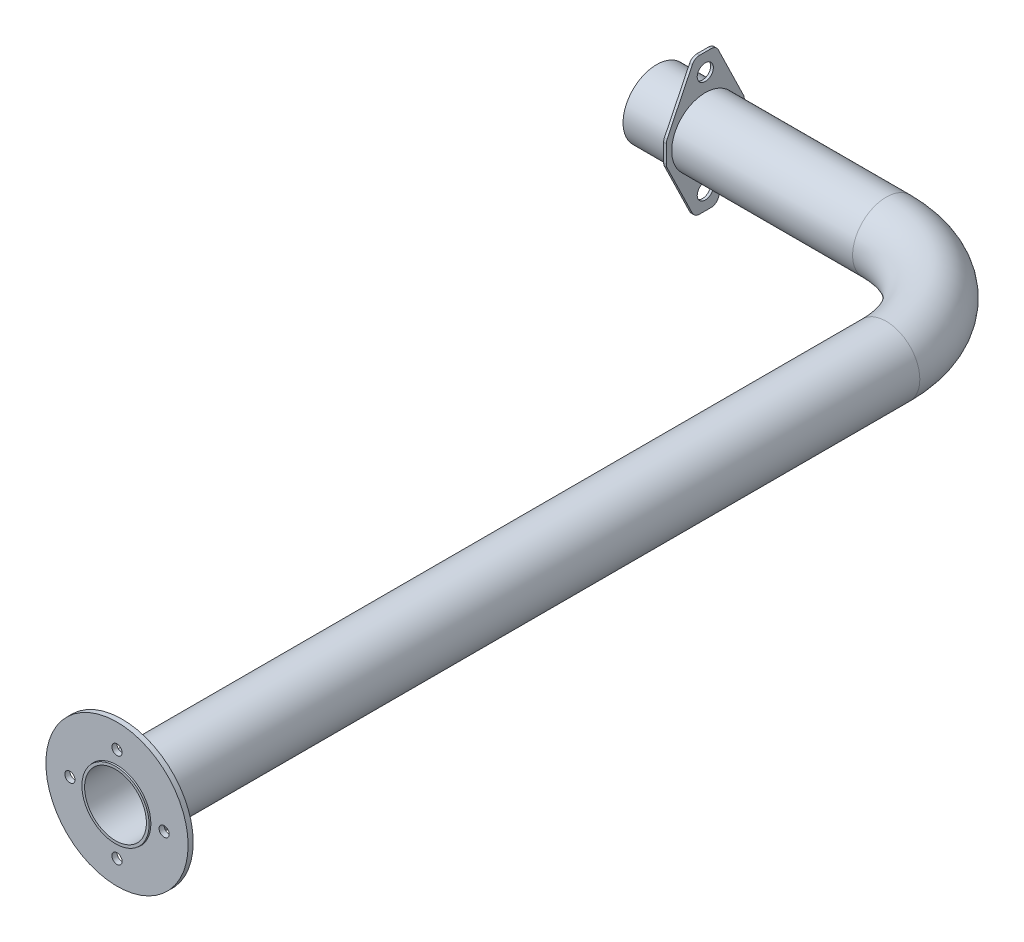
SolidWorks part; units mm, degrees
ref_plane "Спереди" through (0, 0, 0) normal (0, 0, 1) x (1, 0, 0)
ref_plane "Сверху" through (0, 0, 0) normal (0, 1, 0) x (1, 0, 0)
ref_plane "Справа" through (0, 0, 0) normal (1, 0, 0) x (0, 0, -1)
other "Configuration Table"
sketch "Sketch1" plane through (0, 0, 0) normal (0, 0, 1) x (1, 0, 0)
  circle A0 centre (0, 0) radius 20
  circle A1 centre (0, 0) radius 42
extrude "Boss-Extrude1" add sketch "Sketch1" against normal blind 3
sketch "Sketch3" plane through (0, 0, -3) normal (0, 0, -1) x (-1, 0, 0)
  circle A0 centre (0, 0) radius 22
  circle A1 centre (0, 0) radius 20
sketch "Sketch18" plane through (0, 0, 0) normal (0, 0, 1) x (1, 0, 0)
  circle A0 centre (0, 27.8309) radius 3
  circle A1 centre (27.8309, 0) radius 3
  circle A2 centre (0, -27.8309) radius 3
  circle A3 centre (-27.8309, 0) radius 3
  point P11 (0, 0)
  dimension "D1" = 4
scale "Scale1" scale about centroid uniform scaling yes scale factor 0.63
sketch "Sketch27" plane through (0, 0, 0) normal (0, 0, 1) x (1, 0, 0)
  line L1 (119.9559, -17.2407) -> (89.9559, -17.2407)
  line L2 (119.9559, -17.2407) -> (119.9559, 16.7072)
  line L3 (119.9559, 16.7072) -> (89.9559, 16.7072)
  line L4 (89.9559, -17.2407) -> (89.9559, 16.7072)
  dimension "D1" = 30
sketch3d "3DSketch2"
  line L0 (0, 0, 0) -> (0, 0, -286.7)
  line L1 (-40, 0, -326.7) -> (-125.4, 0, -326.7)
  arc A0 (-40, 0, -326.7) -> (0, 0, -286.7) centre (-40, 0, -286.7) ccw
  point P6 (0, 0, -326.7)
  point P7 (-40, -40, -286.7)
  dimension "D1" = 40
ref_plane "Plane1" through (-125.4, 0, 0) normal (1, 0, 0) x (0, 0, -1)
sketch "Sketch45" plane through (-125.4, 0, 0) normal (1, 0, 0) x (0, 0, -1)
  circle A0 centre (326.7, 0) radius 11.5
sweep "Sweep-Thin1" add profiles "Sketch45" path "3DSketch2" parameters "D1"=1
sketch "Sketch47" plane through (0, 0, -2.445) normal (0, 0, -1) x (-1, 0, 0)
  line L0 (0, 0) -> (17.53, 0)
  line L1 (0, 0) -> (0, 17.53)
  circle A0 centre (0, 17.53) radius 1.89
  circle A1 centre (17.53, 0) radius 1.89
  circle A2 centre (0, -17.53) radius 1.89
  circle A3 centre (-17.53, 0) radius 1.89
extrude "Cut-Extrude1" cut sketch "Sketch47" against normal blind 10
sketch "Sketch49" plane through (0, 0, 0) normal (0, 1, 0) x (1, 0, 0)
  line L0 (0, 0) -> (0, 326.7)
  line L1 (0, 326.7) -> (-125.4, 326.7)
ref_plane "Plane2" through (-108.3, 0, 0) normal (1, 0, 0) x (0, 0, -1)
sketch "Sketch50" plane through (-108.3, 0, 0) normal (1, 0, 0) x (0, 0, -1)
  line L0 (326.7, 0) -> (326.7, 19.1)
  line L1 (326.7, 0) -> (337.4941, 0)
  line L2 (326.7, -19.1) -> (326.7, -25.6)
  line L3 (326.7, 19.1) -> (326.7, 25.6)
  line L4 (338.2, 0) -> (341.2, 0)
  line L5 (324.5773, 25.6) -> (328.8227, 25.6)
  line L6 (341.2, -3.3095) -> (341.2, 3.3095)
  line L7 (331.5208, 23.9116) -> (340.8981, 4.621)
  line L8 (331.5208, -23.9116) -> (340.8981, -4.621)
  line L9 (324.5773, -25.6) -> (328.8227, -25.6)
  line L10 (321.8792, -23.9116) -> (312.5019, -4.621)
  line L11 (312.2, -3.3095) -> (312.2, 3.3095)
  line L12 (321.8792, 23.9116) -> (312.5019, 4.621)
  circle A0 centre (326.7, 19.1) radius 3
  circle A1 centre (326.7, 0) radius 11.5
  circle A2 centre (326.7, -19.1) radius 3
  arc A3 (340.8981, 4.621) -> (341.2, 3.3095) centre (338.2, 3.3095) cw
  arc A4 (328.8227, 25.6) -> (331.5208, 23.9116) centre (328.8227, 22.6) cw
  arc A5 (340.8981, -4.621) -> (341.2, -3.3095) centre (338.2, -3.3095) ccw
  arc A6 (328.8227, -25.6) -> (331.5208, -23.9116) centre (328.8227, -22.6) ccw
  arc A7 (324.5773, -25.6) -> (321.8792, -23.9116) centre (324.5773, -22.6) cw
  arc A8 (312.5019, -4.621) -> (312.2, -3.3095) centre (315.2, -3.3095) cw
  arc A9 (312.5019, 4.621) -> (312.2, 3.3095) centre (315.2, 3.3095) ccw
  arc A10 (324.5773, 25.6) -> (321.8792, 23.9116) centre (324.5773, 22.6) ccw
  dimension "D1" = 3
extrude "Boss-Extrude2" add sketch "Sketch50" along normal blind 1 separate body
